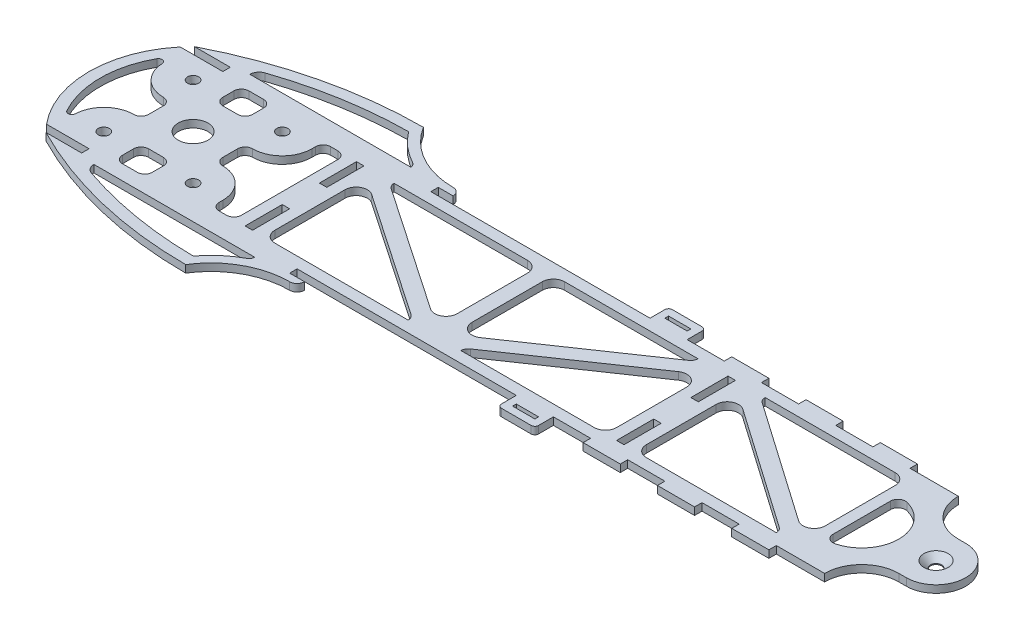
SolidWorks part; units mm, degrees
ref_plane "Front Plane" through (0, 0, 0) normal (0, 0, 1) x (1, 0, 0)
ref_plane "Top Plane" through (0, 0, 0) normal (0, 1, 0) x (1, 0, 0)
ref_plane "Right Plane" through (0, 0, 0) normal (1, 0, 0) x (0, 0, -1)
sketch "Sketch1" plane through (0, 0, 0) normal (0, 1, 0) x (1, 0, 0)
  line L0 (-19.5959, 20) -> (-10, 20)
  line L1 (-40, 0) -> (219.75, 0) construction
  line L2 (-21.4476, 18) -> (-10, 18)
  line L3 (20, 12) -> (20, 13)
  line L4 (22, 15) -> (24, 15)
  line L5 (26, 13) -> (26, -13)
  line L6 (50, 20) -> (46, 20)
  line L7 (10, 2) -> (10, -2)
  line L8 (46, 20) -> (46, 18)
  line L9 (-10, 2) -> (-10, -2)
  line L10 (-4, 15) -> (-4, 12)
  line L11 (4, 15) -> (4, 12)
  line L12 (-2, 10) -> (2, 10)
  line L13 (-2, 17) -> (2, 17)
  line L14 (46, 18) -> (105, 18)
  line L15 (-10, 18) -> (-10, 20)
  line L16 (-5.706, 21) -> (37.5752, 21)
  line L17 (105, 18) -> (105, 22)
  line L18 (29, 15) -> (31, 15)
  line L19 (29, 15) -> (29, 5)
  line L20 (29, 5) -> (31, 5)
  line L21 (31, 15) -> (31, 5)
  line L22 (106, 23) -> (114, 23)
  line L23 (115, 22) -> (115, 18)
  line L24 (115, 18) -> (125, 18)
  line L25 (135, 18) -> (145, 18)
  line L26 (107, 21) -> (113, 21)
  line L27 (107, 21) -> (107, 20)
  line L28 (107, 20) -> (113, 20)
  line L29 (113, 21) -> (113, 20)
  line L30 (155, 18) -> (165, 18)
  line L31 (125, 18) -> (125, 20)
  line L32 (125, 20) -> (135, 20)
  line L33 (135, 18) -> (135, 20)
  line L34 (175, 18) -> (188, 18)
  line L35 (145, 18) -> (145, 20)
  line L36 (145, 20) -> (155, 20)
  line L37 (155, 18) -> (155, 20)
  line L38 (200, 8) -> (198, 8)
  line L39 (165, 18) -> (165, 20)
  line L40 (165, 20) -> (175, 20)
  line L41 (175, 18) -> (175, 20)
  line L42 (180, 7.746) -> (180, -7.746)
  line L43 (175, -18) -> (175, -20)
  line L44 (165, -20) -> (175, -20)
  line L45 (165, -18) -> (165, -20)
  line L46 (200, -8) -> (198, -8)
  line L47 (155, -18) -> (155, -20)
  line L48 (145, -20) -> (155, -20)
  line L49 (145, -18) -> (145, -20)
  line L50 (175, -18) -> (188, -18)
  line L51 (135, -18) -> (135, -20)
  line L52 (125, -20) -> (135, -20)
  line L53 (125, -18) -> (125, -20)
  line L54 (155, -18) -> (165, -18)
  line L55 (113, -21) -> (113, -20)
  line L56 (107, -20) -> (113, -20)
  line L57 (107, -21) -> (107, -20)
  line L58 (107, -21) -> (113, -21)
  line L59 (135, -18) -> (145, -18)
  line L60 (115, -18) -> (125, -18)
  line L61 (115, -22) -> (115, -18)
  line L62 (106, -23) -> (114, -23)
  line L63 (31, -15) -> (31, -5)
  line L64 (29, -5) -> (31, -5)
  line L65 (29, -15) -> (29, -5)
  line L66 (29, -15) -> (31, -15)
  line L67 (105, -18) -> (105, -22)
  line L68 (-5.706, -21) -> (37.5752, -21)
  line L69 (-10, -18) -> (-10, -20)
  line L70 (46, -18) -> (105, -18)
  line L71 (-2, -17) -> (2, -17)
  line L72 (-2, -10) -> (2, -10)
  line L73 (4, -15) -> (4, -12)
  line L74 (-4, -15) -> (-4, -12)
  line L75 (46, -20) -> (46, -18)
  line L76 (50, -20) -> (46, -20)
  line L77 (22, -15) -> (24, -15)
  line L78 (20, -12) -> (20, -13)
  line L79 (-21.4476, -18) -> (-10, -18)
  line L80 (-19.5959, -20) -> (-10, -20)
  line L81 (139.8464, 13.3597) -> (172.2835, -9.2707)
  line L82 (39.1005, 15) -> (75, 15)
  line L83 (34, 6.9029) -> (34, -12)
  line L84 (37, -15) -> (72.8995, -15)
  line L85 (78, 12) -> (78, -6.9029)
  line L86 (0, 0) -> (16.6525, 16.6525) construction
  line L87 (38.69, 9.3816) -> (72.0261, -13.3475)
  line L88 (85, 15) -> (120.8995, 15)
  line L89 (39.9739, 13.3475) -> (73.31, -9.3816)
  line L90 (82, 12) -> (82, -6.9029)
  line L91 (138.9908, 15) -> (174, 15)
  line L92 (126, 6.9029) -> (126, -12)
  line L94 (129, 15) -> (131, 15)
  line L95 (129, 15) -> (129, 5)
  line L96 (129, 5) -> (131, 5)
  line L97 (131, 15) -> (131, 5)
  line L98 (129, -5) -> (131, -5)
  line L99 (129, -5) -> (129, -15)
  line L100 (129, -15) -> (131, -15)
  line L101 (131, -5) -> (131, -15)
  line L103 (134, 6.8104) -> (134, -12)
  line L104 (137, -15) -> (172.0092, -15)
  line L105 (177, 12) -> (177, -6.8104)
  line L107 (138.7165, 9.2707) -> (171.1536, -13.3597)
  line L108 (86.69, -9.3816) -> (120.0261, 13.3475)
  line L110 (87.9739, -13.3475) -> (121.31, 9.3816)
  line L114 (87.1005, -15) -> (123, -15)
  circle A0 centre (0, 0) radius 4
  arc A1 (-21.4476, 18) -> (-21.4476, -18) centre (0, 0) ccw
  circle A2 centre (12.0208, 12.0208) radius 1.5
  arc A3 (-21.8672, 12.1172) -> (-21.8672, -12.1172) centre (0, 0) ccw
  arc A4 (30, 32) -> (-19.5959, 20) centre (30, -76.4898) ccw
  arc A5 (-19.9933, 11.6733) -> (-12, 4) centre (-12, 12) ccw
  circle A6 centre (12.0208, -12.0208) radius 1.5
  arc A7 (12, 4) -> (20, 12) centre (12, 12) ccw
  arc A8 (-19.9933, 11.6733) -> (-21.8672, 12.1172) centre (-20.9925, 11.6325) ccw
  arc A9 (-2, 17) -> (-4, 15) centre (-2, 15) ccw
  arc A10 (2, 17) -> (4, 15) centre (2, 15) cw
  arc A11 (2, 10) -> (4, 12) centre (2, 12) ccw
  arc A12 (-2, 10) -> (-4, 12) centre (-2, 12) cw
  arc A13 (29.0284, 28.9955) -> (-4.012, 23.3665) centre (30, -76.4898) ccw
  arc A14 (24, 15) -> (26, 13) centre (24, 13) cw
  arc A15 (30, 29) -> (-18.2245, 17.3318) centre (30, -76.4898) ccw construction
  arc A16 (20, 13) -> (22, 15) centre (22, 13) cw
  arc A17 (-10, 2) -> (-12, 4) centre (-12, 2) ccw
  arc A18 (12, 4) -> (10, 2) centre (12, 2) ccw
  arc A19 (50, 20) -> (48, 22) centre (48, 20) ccw
  arc A20 (30, 32) -> (48, 22) centre (48, 43.2) ccw
  arc A21 (29.0284, 28.9955) -> (36.785, 22.3214) centre (48, 43.2) ccw
  arc A22 (37.5752, 21) -> (36.785, 22.3214) centre (36.0752, 21) ccw
  arc A23 (27.8774, 30.6792) -> (48, 19.5) centre (48, 43.2) ccw construction
  arc A24 (-4.012, 23.3665) -> (-5.706, 21) centre (-3.206, 21) ccw
  arc A25 (114, 23) -> (115, 22) centre (114, 22) cw
  arc A26 (105, 22) -> (106, 23) centre (106, 22) cw
  circle A27 centre (200, 0) radius 1.5
  arc A28 (200, -8) -> (200, 8) centre (200, 0) ccw
  arc A29 (188, 18) -> (198, 8) centre (198, 18) ccw
  arc A30 (182.5, -9.6825) -> (182.5, 9.6825) centre (180, 0) ccw
  arc A31 (180, 7.746) -> (182.5, 9.6825) centre (182, 7.746) cw
  arc A32 (180, -7.746) -> (182.5, -9.6825) centre (182, -7.746) ccw
  arc A33 (188, -18) -> (198, -8) centre (198, -18) cw
  arc A34 (105, -22) -> (106, -23) centre (106, -22) ccw
  arc A35 (114, -23) -> (115, -22) centre (114, -22) ccw
  arc A36 (-4.012, -23.3665) -> (-5.706, -21) centre (-3.206, -21) cw
  arc A37 (37.5752, -21) -> (36.785, -22.3214) centre (36.0752, -21) cw
  arc A38 (29.0284, -28.9955) -> (36.785, -22.3214) centre (48, -43.2) cw
  arc A39 (30, -32) -> (48, -22) centre (48, -43.2) cw
  arc A40 (50, -20) -> (48, -22) centre (48, -20) cw
  arc A41 (12, -4) -> (10, -2) centre (12, -2) cw
  arc A42 (-10, -2) -> (-12, -4) centre (-12, -2) cw
  arc A43 (20, -13) -> (22, -15) centre (22, -13) ccw
  arc A44 (24, -15) -> (26, -13) centre (24, -13) ccw
  arc A45 (29.0284, -28.9955) -> (-4.012, -23.3665) centre (30, 76.4898) cw
  arc A46 (-2, -10) -> (-4, -12) centre (-2, -12) ccw
  arc A47 (2, -10) -> (4, -12) centre (2, -12) cw
  arc A48 (2, -17) -> (4, -15) centre (2, -15) ccw
  arc A49 (-2, -17) -> (-4, -15) centre (-2, -15) cw
  arc A50 (-19.9933, -11.6733) -> (-21.8672, -12.1172) centre (-20.9925, -11.6325) cw
  arc A51 (12, -4) -> (20, -12) centre (12, -12) cw
  circle A52 centre (-12.0208, -12.0208) radius 1.5
  arc A53 (-19.9933, -11.6733) -> (-12, -4) centre (-12, -12) cw
  arc A54 (30, -32) -> (-19.5959, -20) centre (30, 76.4898) cw
  circle A55 centre (-12.0208, 12.0208) radius 1.5
  arc A56 (39.1005, 15) -> (39.9739, 13.3475) centre (41.1005, 15) ccw
  arc A57 (72.8995, -15) -> (72.0261, -13.3475) centre (70.8995, -15) ccw
  arc A58 (34, 6.9029) -> (38.69, 9.3816) centre (37, 6.9029) cw
  arc A59 (34, -12) -> (37, -15) centre (37, -12) ccw
  arc A60 (78, -6.9029) -> (73.31, -9.3816) centre (75, -6.9029) cw
  arc A61 (75, 15) -> (78, 12) centre (75, 12) cw
  arc A62 (120.0261, 13.3475) -> (120.8995, 15) centre (118.8995, 15) ccw
  arc A63 (87.9739, -13.3475) -> (87.1005, -15) centre (89.1005, -15) ccw
  arc A64 (172.0092, -15) -> (171.1536, -13.3597) centre (170.0092, -15) ccw
  arc A65 (138.9908, 15) -> (139.8464, 13.3597) centre (140.9908, 15) ccw
  arc A66 (177, -6.8104) -> (172.2835, -9.2707) centre (174, -6.8104) cw
  arc A67 (174, 15) -> (177, 12) centre (174, 12) cw
  arc A68 (134, 6.8104) -> (138.7165, 9.2707) centre (137, 6.8104) cw
  arc A69 (134, -12) -> (137, -15) centre (137, -12) ccw
  arc A70 (123, -15) -> (126, -12) centre (123, -12) ccw
  arc A71 (126, 6.9029) -> (121.31, 9.3816) centre (123, 6.9029) ccw
  arc A72 (85, 15) -> (82, 12) centre (85, 12) ccw
  arc A73 (82, -6.9029) -> (86.69, -9.3816) centre (85, -6.9029) ccw
  point P28 (180, -10)
  point P31 (26, 0)
  point P82 (115, 23)
  point P85 (105, 23)
  point P109 (180, 10)
  point P193 (-10, 0)
  point P194 (10, 0)
  point P195 (105, -23)
  point P196 (115, -23)
  point P197 (34, 15)
  point P198 (78, -15)
  point P201 (32.8733, 13.3475)
  point P203 (76.8733, -16.6525)
  point P204 (35.1267, 16.6525)
  point P205 (79.1267, -13.3475)
  point P224 (82, -15)
  point P225 (126, 15)
  point P234 (134, 15)
  point P235 (177, -15)
  point P238 (83.1267, -16.6525)
  point P239 (127.1267, 13.3475)
  point P240 (132.8556, 13.3597)
  point P241 (175.8556, -16.6403)
  point P242 (80.8733, -13.3475)
  point P243 (124.8733, 16.6525)
  point P244 (135.1444, 16.6403)
  point P245 (178.1444, -13.3597)
  point P285 (0, 0)
  dimension "D1" = 16
  dimension "D2" = 2
  dimension "D3" = 2
  dimension "D5" = 2
  dimension "D6" = 4
  dimension "D7" = 4
  dimension "D9" = 3
  dimension "D10" = 5
  dimension "D14" = 1
  dimension "D15" = 2
  dimension "D18" = 4
  dimension "D17" = 4
  dimension "D16" = 3
  dimension "D21" = 4
  dimension "D22" = 4
  dimension "D23" = 4
  dimension "D24" = 4
  dimension "D19" = 3
  dimension "D20" = 3
  dimension "D25" = 3
  dimension "D11" = 5
  dimension "D12" = 10
  dimension "D13" = 105
  dimension "D26" = 17
  dimension "D4" = 3
  dimension "D8" = 2.5
  dimension "D27" = 4
extrude "Boss-Extrude1" add sketch "Sketch1" along normal blind 2
chamfer "Chamfer1" distance 1.75 angle 45 1 edges at (200, 2, 1.5)
